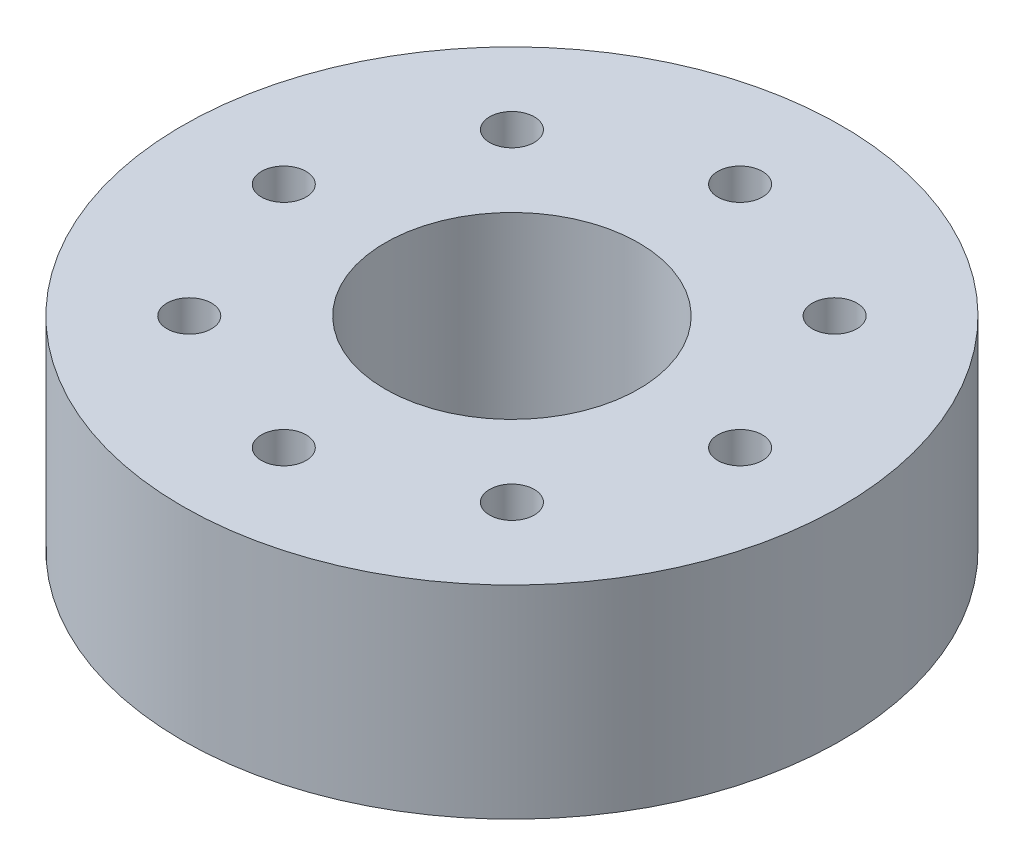
SolidWorks part; units mm, degrees
ref_plane "Front Plane" through (0, 0, 0) normal (0, 0, 1) x (1, 0, 0)
ref_plane "Top Plane" through (0, 0, 0) normal (0, 1, 0) x (1, 0, 0)
ref_plane "Right Plane" through (0, 0, 0) normal (1, 0, 0) x (0, 0, -1)
sketch "Sketch1" plane through (0, 0, 0) normal (0, 1, 0) x (1, 0, 0)
  circle A0 centre (0, 0) radius 32.5
  dimension "D1" = 65
extrude "Boss-Extrude1" add sketch "Sketch1" along normal blind 20
sketch "Sketch2" plane through (0, 20, 0) normal (0, 1, 0) x (1, 0, 0)
  line L0 (0, -11) -> (0, 11) construction
  line L1 (-11, 0) -> (11, 0) construction
  circle A0 centre (0, 22.5) radius 2.2
  circle A1 centre (15.9099, 15.9099) radius 2.2
  circle A2 centre (22.5, 0) radius 2.2
  circle A3 centre (15.9099, -15.9099) radius 2.2
  circle A4 centre (0, -22.5) radius 2.2
  circle A5 centre (-15.9099, -15.9099) radius 2.2
  circle A6 centre (-22.5, 0) radius 2.2
  circle A7 centre (-15.9099, 15.9099) radius 2.2
  point P22 (0, 0)
  dimension "D2" = 4.4
  dimension "D1" = 22.5
  dimension "D3" = 8
extrude "Cut-Extrude1" cut sketch "Sketch2" against normal through all
sketch "Sketch3" plane through (0, 20, 0) normal (0, 1, 0) x (1, 0, 0)
  circle A0 centre (0, 0) radius 12.5
  dimension "D1" = 25
extrude "Cut-Extrude2" cut sketch "Sketch3" against normal through all
